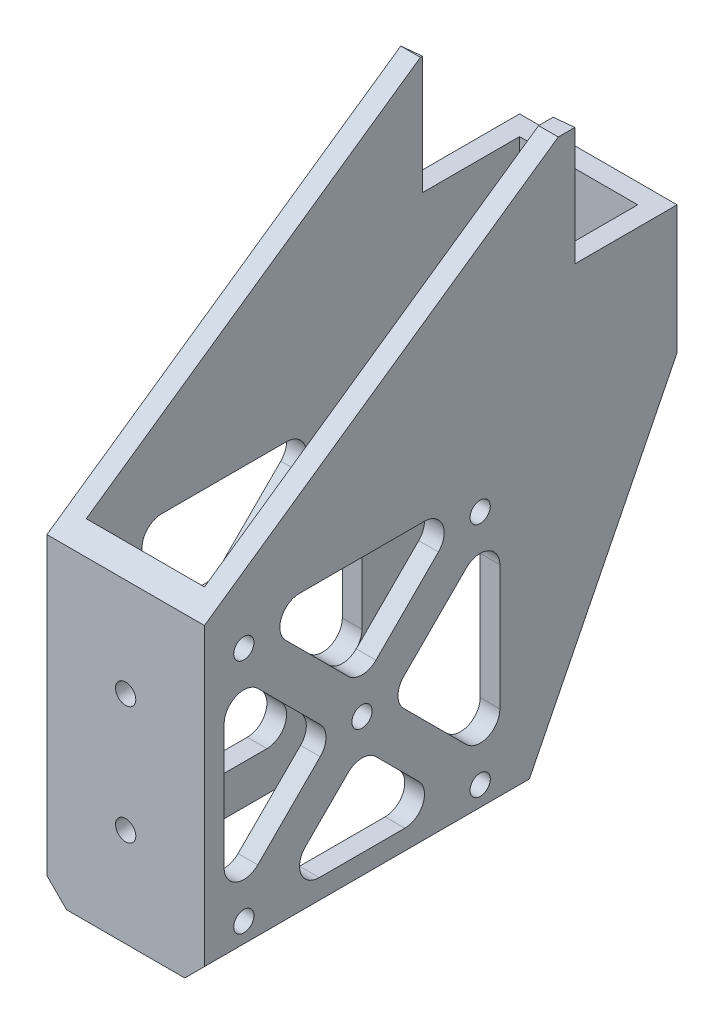
SolidWorks part; units mm, degrees
material "6061-T6 (SS)"
ref_plane "Front Plane" through (0, 0, 0) normal (0, 0, 1) x (1, 0, 0)
ref_plane "Top Plane" through (0, 0, 0) normal (0, 1, 0) x (1, 0, 0)
ref_plane "Right Plane" through (0, 0, 0) normal (1, 0, 0) x (0, 0, -1)
sketch "Sketch1" plane through (0, 0, 0) normal (0, 1, 0) x (1, 0, 0)
  line L1 (-12.7, -38.1) -> (12.7, -38.1)
  line L2 (-12.7, -38.1) -> (-12.7, 38.1)
  line L3 (-12.7, 38.1) -> (12.7, 38.1)
  line L4 (12.7, -38.1) -> (12.7, 38.1)
  line L5 (-12.7, -38.1) -> (12.7, 38.1) construction
  line L6 (-12.7, 38.1) -> (12.7, -38.1) construction
  line L7 (-9.525, -34.925) -> (9.525, -34.925)
  line L8 (-9.525, -34.925) -> (-9.525, 34.925)
  line L9 (-9.525, 34.925) -> (9.525, 34.925)
  line L10 (9.525, -34.925) -> (9.525, 34.925)
  line L11 (-9.525, -34.925) -> (9.525, 34.925) construction
  line L12 (-9.525, 34.925) -> (9.525, -34.925) construction
  point P0 (0, 0)
  point P6 (0, 0)
  dimension "D1" = 25.4
  dimension "D2" = 19.05
  dimension "D3" = 76.2
  dimension "D4" = 69.85
extrude "Boss-Extrude1" add sketch "Sketch1" along normal blind 90.4875
sketch "Sketch2" plane through (0, 90.4875, 0) normal (0, 1, 0) x (1, 0, 0)
  line L0 (-12.7, 38.1) -> (-36.83, 35.56) construction
  line L1 (-36.83, 35.56) -> (-12.7, 35.56) construction
  line L2 (-12.7, 38.1) -> (-12.7, -38.1) construction
  line L3 (-12.7, 35.56) -> (-12.7, 38.1) construction
  line L4 (-12.7, 18.9448) -> (12.7, 21.6184)
  line L5 (-12.7, 18.9448) -> (-12.7, 38.1)
  line L6 (12.7, 38.1) -> (12.7, 21.6184)
  line L7 (12.7, -38.1) -> (12.7, 38.1) construction
  line L8 (-12.7, 38.1) -> (12.7, 38.1)
  dimension "D1" = 2.54
  dimension "D2" = 24.13
  dimension "D3" = 19.05
extrude "Cut-Extrude1" cut sketch "Sketch2" against normal blind 19.05
sketch "Sketch3" plane through (-12.7, 0, 0) normal (-1, 0, 0) x (0, 0, 1)
  line L0 (-18.9448, 90.4875) -> (38.1, 50.8)
  line L1 (38.1, 90.4875) -> (38.1, 0) construction
  line L2 (-12.7, 0) -> (-38.1, 50.8)
  line L3 (-38.1, 0) -> (38.1, 0) construction
  line L4 (-38.1, 71.4375) -> (-38.1, 0) construction
  line L5 (-12.7, 0) -> (-12.7, 50.8) construction
  line L6 (-12.7, 50.8) -> (38.1, 50.8) construction
  line L7 (38.1, 50.8) -> (-12.7, 0) construction
  line L8 (-12.7, 50.8) -> (38.1, 0) construction
  line L9 (-4.1049, 37.7148) -> (5.9648, 27.6451)
  line L10 (5.9648, 23.1549) -> (-4.1049, 13.0852)
  line L11 (-9.525, 15.3303) -> (-9.525, 35.4697)
  line L12 (0.3852, 42.2049) -> (10.4549, 32.1352)
  line L13 (14.9451, 32.1352) -> (25.0148, 42.2049)
  line L14 (22.7697, 47.625) -> (2.6303, 47.625)
  line L15 (12.7, 25.4) -> (38.1, 25.4) construction
  line L16 (12.7, 25.4) -> (12.7, -7.1437) construction
  line L17 (5.8053, 6.35) -> (19.5947, 6.35)
  line L18 (14.9451, 18.6648) -> (21.8398, 11.7701)
  line L19 (3.5602, 11.7701) -> (10.4549, 18.6648)
  line L20 (34.925, 15.3303) -> (34.925, 35.4697)
  line L21 (19.4352, 23.1549) -> (29.5049, 13.0852)
  line L22 (29.5049, 37.7148) -> (19.4352, 27.6451)
  arc A0 (-9.525, 15.3303) -> (-4.1049, 13.0852) centre (-6.35, 15.3303) ccw
  arc A1 (3.5602, 11.7701) -> (5.8053, 6.35) centre (5.8053, 9.525) ccw
  arc A2 (21.8398, 11.7701) -> (19.5947, 6.35) centre (19.5947, 9.525) cw
  arc A3 (34.925, 15.3303) -> (29.5049, 13.0852) centre (31.75, 15.3303) cw
  arc A4 (34.925, 35.4697) -> (29.5049, 37.7148) centre (31.75, 35.4697) ccw
  arc A5 (25.0148, 42.2049) -> (22.7697, 47.625) centre (22.7697, 44.45) ccw
  arc A6 (0.3852, 42.2049) -> (2.6303, 47.625) centre (2.6303, 44.45) cw
  arc A7 (-9.525, 35.4697) -> (-4.1049, 37.7148) centre (-6.35, 35.4697) cw
  arc A8 (10.4549, 18.6648) -> (14.9451, 18.6648) centre (12.7, 16.4197) cw
  arc A9 (19.4352, 23.1549) -> (19.4352, 27.6451) centre (21.6803, 25.4) cw
  arc A10 (14.9451, 32.1352) -> (10.4549, 32.1352) centre (12.7, 34.3803) cw
  arc A11 (5.9648, 23.1549) -> (5.9648, 27.6451) centre (3.7197, 25.4) ccw
  point P11 (31.75, 6.35)
  point P13 (-6.35, 6.35)
  point P14 (12.7, 25.4)
  point P15 (-6.35, 44.45)
  point P16 (31.75, 44.45)
  point P36 (-9.525, 7.6651)
  point P39 (-5.0349, 3.175)
  point P42 (30.4349, 3.175)
  point P45 (34.925, 7.6651)
  point P48 (34.925, 43.1349)
  point P51 (30.4349, 47.625)
  point P54 (-5.0349, 47.625)
  point P57 (-9.525, 43.1349)
  point P60 (12.7, 20.9099)
  point P63 (17.1901, 25.4)
  point P66 (12.7, 29.8901)
  point P69 (8.2099, 25.4)
  line M1 (38.1, 90.4875) -> (-18.9448, 90.4875)
  line M4 (-38.1, 71.4375) -> (-38.1, 0)
  line M5 (-38.1, 0) -> (38.1, 0)
  line M6 (38.1, 0) -> (38.1, 90.4875)
  dimension "D11" = 3.175
  dimension "D13" = 3.175
  dimension "D1" = 39.6875
  dimension "D2" = 50.8
  dimension "D3" = 25.4
  dimension "D4" = 6.35
  dimension "D5" = 6.35
  dimension "D6" = 3.175
  dimension "D7" = 3.175
  dimension "D8" = 3.175
  dimension "D9" = 6.35
  dimension "D10" = 3.175
  dimension "D12" = 6.35
extrude "Cut-Extrude2" cut sketch "Sketch3" against normal through all contours L0 M1 M6 | L13 L14 L12 | L11 L10 L9 | L19 L17 L18 | L20 L22 L21 | L2 M5 M4
hole_wizard "#30 (0.1285) Diameter Hole1" positions "Sketch5" profile "Sketch6" hole size "#30" standard "ANSI Inch" end condition through all
sketch "Sketch5" plane through (-12.7, 0, 0) normal (-1, 0, 0) x (0, 0, 1)
  point P0 (-6.35, 44.45)
  point P3 (12.7, 25.4)
  point P6 (31.75, 44.45)
  point P9 (31.75, 6.35)
  point P12 (-6.35, 6.35)
sketch "Sketch6" plane through (-12.7, 44.45, -6.35) normal (0, 1, 0) x (0, 0, 1)
  line L0 (0, 0) -> (0, 25.4)
  line L1 (0, 25.4) -> (1.6319, 25.4)
  line L2 (1.6319, 25.4) -> (1.6319, 0)
  line L5 (1.6319, 0) -> (0, 0)
  line L11 (0, -6.35) -> (0, 107.95) construction
  dimension "Thru Hole Dia." = 3.2639
  dimension "Thru Hole Depth" = 25.4
sketch "Sketch7" plane through (0, 0, 38.1) normal (0, 0, 1) x (1, 0, 0)
  line L0 (0, 0) -> (0, 50.8) construction
  line L1 (-12.7, 0) -> (12.7, 0) construction
  line L2 (12.7, 50.8) -> (-12.7, 50.8) construction
  line L3 (-12.7, 50.8) -> (12.7, 50.8) construction
  line L4 (-12.7, 50.8) -> (-12.7, 0) construction
  line L5 (12.7, 50.8) -> (12.7, 0) construction
  point P12 (0, 34.925)
  point P13 (0, 15.875)
  dimension "D1" = 50.8
  dimension "D2" = 15.875
  dimension "D3" = 15.875
hole_wizard "#30 (0.1285) Diameter Hole2" positions "Sketch9" profile "Sketch8" hole size "#30" standard "ANSI Inch" end condition through all
sketch "Sketch9" plane through (0, 0, 38.1) normal (0, 0, 1) x (1, 0, 0)
  point P0 (0, 34.925)
  point P3 (0, 15.875)
sketch "Sketch8" plane through (0, 34.925, 38.1) normal (1, 0, 0) x (0, -1, 0)
  line L0 (0, 0) -> (0, 76.2)
  line L1 (0, 76.2) -> (1.6319, 76.2)
  line L2 (1.6319, 76.2) -> (1.6319, 0)
  line L5 (1.6319, 0) -> (0, 0)
  line L11 (0, -6.35) -> (0, 107.95) construction
  dimension "Thru Hole Dia." = 3.2639
  dimension "Thru Hole Depth" = 76.2
chamfer "Chamfer1" distance 3.175 angle 45 2 edges at (12.7, 0, 12.7) (-12.7, 0, 12.7)
